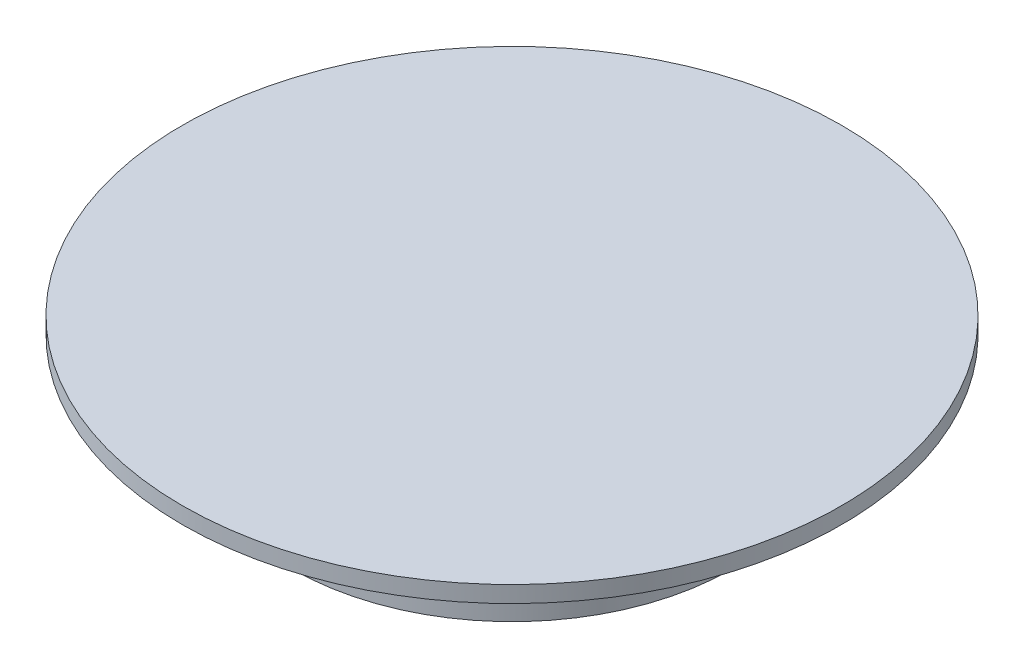
SolidWorks part; units mm, degrees
ref_plane "Front Plane" through (0, 0, 0) normal (0, 0, 1) x (1, 0, 0)
ref_plane "Top Plane" through (0, 0, 0) normal (0, 1, 0) x (1, 0, 0)
ref_plane "Right Plane" through (0, 0, 0) normal (1, 0, 0) x (0, 0, -1)
sketch "Sketch1" plane through (0, 0, 0) normal (0, 0, 1) x (1, 0, 0)
  line L0 (-40, 20) -> (-60, 20)
  line L1 (0, -63.9535) -> (0, 73.7209) construction
  line L2 (-40, 20) -> (0, 20)
  line L3 (0, 20) -> (0, 17)
  line L4 (0, 17) -> (-35, 17)
  line L5 (-60, 20) -> (-60, 17)
  line L7 (-35, 17) -> (-35, 0)
  line L8 (-35, 0) -> (-40, 0)
  line L9 (-40, 0) -> (-40, 17)
  line L10 (-60, 17) -> (-40, 17)
  line L11 (-40, 17) -> (-40, 20) construction
  line L12 (-40, 17) -> (-35, 17) construction
  dimension "D1" = 3
  dimension "D2" = 20
  dimension "D3" = 60
  dimension "D6" = 40
  dimension "D7" = 5
revolve "Revolve1" add sketch "Sketch1" angle 360 about L1
ref_plane "Plane1" through (0, 0, 40) normal (0, 0, 1) x (1, 0, 0)
fillet "Fillet1" radius 3 1 edges at (0, 17, -40)
